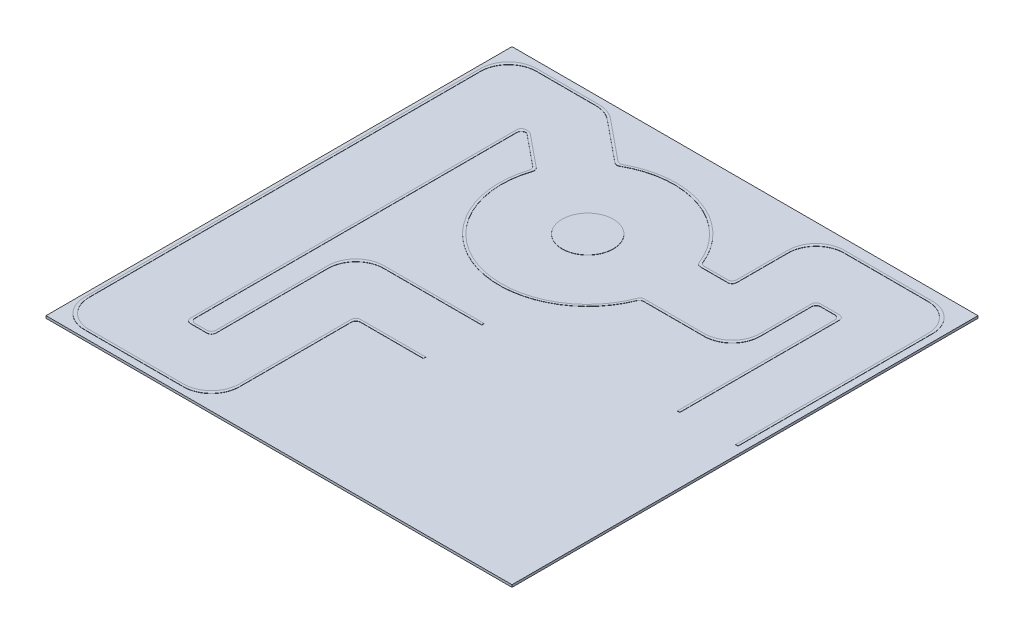
SolidWorks part; units mm, degrees
ref_plane "Plan de face" through (0, 0, 0) normal (0, 0, 1) x (1, 0, 0)
ref_plane "Plan de dessus" through (0, 0, 0) normal (0, 1, 0) x (1, 0, 0)
ref_plane "Plan de droite" through (0, 0, 0) normal (1, 0, 0) x (0, 0, -1)
sketch "Esquisse1" plane through (0, 0, 0) normal (0, 1, 0) x (1, 0, 0)
  line L0 (840, 0) -> (840, 825) construction
  line L1 (-1000, 1000) -> (1000, 1000)
  line L2 (-1000, 1000) -> (-1000, -1000)
  line L3 (-1000, -1000) -> (1000, -1000)
  line L4 (1000, 1000) -> (1000, -1000)
  line L5 (840, 825) -> (480, 825) construction
  line L6 (480, 825) -> (480, 465) construction
  line L7 (480, 465) -> (-140, 465) construction
  line L8 (-140, 465) -> (-600, 840) construction
  line L9 (-600, 840) -> (-800, 840) construction
  line L10 (-800, 840) -> (-800, -840) construction
  line L11 (-800, -840) -> (-450, -840) construction
  line L12 (-450, -840) -> (-450, -220) construction
  line L13 (-450, -220) -> (-30, -220) construction
  line L14 (720, 0) -> (720, 685)
  line L15 (700, 705) -> (620, 705)
  line L16 (600, 685) -> (600, 465)
  line L17 (480, 345) -> (224.0055, 345)
  line L18 (710, 0) -> (710, 675)
  line L19 (690, 695) -> (630, 695)
  line L20 (610, 675) -> (610, 455)
  line L21 (490, 335) -> (230.8099, 335)
  line L22 (710, 0) -> (710, 695) construction
  line L23 (960, 0) -> (960, 825)
  line L24 (840, 945) -> (480, 945)
  line L25 (360, 825) -> (360, 605)
  line L26 (340, 585) -> (224.0055, 585)
  line L27 (970, 0) -> (970, 835)
  line L28 (850, 955) -> (470, 955)
  line L29 (350, 835) -> (350, 615)
  line L30 (330, 595) -> (230.8099, 595)
  line L31 (-30, -340) -> (-310, -340)
  line L32 (-330, -360) -> (-330, -840)
  line L33 (-450, -960) -> (-855, -960)
  line L34 (-975, -840) -> (-975, 840)
  line L35 (-855, 960) -> (-600, 960)
  line L36 (-524.1767, 933.0099) -> (-346.3109, 788.0105)
  line L37 (-30, -100) -> (-450, -100)
  line L38 (-570, -220) -> (-570, -700)
  line L39 (-590, -720) -> (-660, -720)
  line L40 (-680, -700) -> (-680, 700)
  line L41 (-660, 720) -> (-649.8346, 720)
  line L42 (-637.1974, 715.5016) -> (-497.9574, 601.9908)
  line L43 (710, 0) -> (720, 0)
  line L44 (960, 0) -> (970, 0)
  line L45 (-30, -90) -> (-460, -90)
  line L46 (-580, -210) -> (-580, -690)
  line L47 (-600, -710) -> (-650, -710)
  line L48 (-670, -690) -> (-670, 690)
  line L49 (-650, 710) -> (-646.275, 710)
  line L50 (-646.275, 710) -> (-509.55, 598.5394)
  line L51 (-30, -350) -> (-300, -350)
  line L52 (-320, -370) -> (-320, -850)
  line L53 (-440, -970) -> (-865, -970)
  line L54 (-985, -850) -> (-985, 850)
  line L55 (-865, 970) -> (-596.4404, 970)
  line L56 (-520.6171, 943.0099) -> (-345.2663, 800.0608)
  line L57 (-30, -90) -> (-30, -100)
  line L58 (-30, -340) -> (-30, -350)
  line L59 (-553.725, 970) -> (-329.1369, 786.9118) construction
  line L60 (-646.275, 710) -> (-493.4206, 585.3905) construction
  line L61 (350, 595) -> (210, 595) construction
  line L62 (610, 335) -> (210, 335) construction
  line L63 (960, 0) -> (960, 945) construction
  line L64 (960, 945) -> (360, 945) construction
  line L65 (970, 0) -> (970, 955) construction
  line L66 (970, 955) -> (350, 955) construction
  line L67 (350, 955) -> (350, 595) construction
  line L68 (360, 945) -> (360, 585) construction
  line L69 (610, 695) -> (610, 335) construction
  line L70 (600, 705) -> (600, 345) construction
  line L71 (600, 345) -> (210, 345) construction
  line L72 (-30, -100) -> (-570, -100) construction
  line L73 (-570, -100) -> (-570, -720) construction
  line L74 (-30, -90) -> (-580, -90) construction
  line L75 (-580, -90) -> (-580, -710) construction
  line L76 (-330, -340) -> (-330, -960) construction
  line L77 (-330, -960) -> (-975, -960) construction
  line L78 (-320, -350) -> (-320, -970) construction
  line L79 (-320, -970) -> (-985, -970) construction
  line L80 (-975, -960) -> (-975, 960) construction
  line L81 (-985, -970) -> (-985, 970) construction
  line L82 (-985, 970) -> (-553.725, 970) construction
  line L83 (-975, 960) -> (-557.2847, 960) construction
  line L84 (-557.2847, 960) -> (-335.4555, 779.161) construction
  line L85 (710, 695) -> (610, 695) construction
  line L86 (720, 705) -> (600, 705) construction
  line L87 (720, 0) -> (720, 705) construction
  line L88 (-30, -340) -> (-330, -340) construction
  line L89 (-30, -350) -> (-320, -350) construction
  line L90 (-580, -710) -> (-670, -710) construction
  line L91 (-570, -720) -> (-680, -720) construction
  line L92 (-680, -720) -> (-680, 720) construction
  line L93 (-670, -710) -> (-670, 710) construction
  line L94 (-680, 720) -> (-642.7153, 720) construction
  line L95 (-642.7153, 720) -> (-487.102, 593.1413) construction
  line L96 (-670, 710) -> (-646.275, 710) construction
  line L97 (360, 585) -> (210, 585) construction
  circle A0 centre (-140, 465) radius 110
  circle A1 centre (-140, 465) radius 120
  arc A2 (-491.5898, 580.259) -> (205.3385, 332.1795) centre (-140, 465) ccw
  arc A3 (-503.0779, 577.1359) -> (212.2694, 322.5) centre (-140, 465) ccw
  arc A4 (212.2694, 607.5) -> (-322.9976, 798.0343) centre (-140, 465) ccw
  arc A5 (205.3385, 597.8205) -> (-323.7417, 786.1526) centre (-140, 465) ccw
  arc A6 (960, 825) -> (840, 945) centre (840, 825) ccw
  arc A7 (970, 835) -> (850, 955) centre (850, 835) ccw
  arc A8 (470, 955) -> (350, 835) centre (470, 835) ccw
  arc A9 (480, 945) -> (360, 825) centre (480, 825) ccw
  arc A10 (610, 455) -> (490, 335) centre (490, 455) cw
  arc A11 (600, 465) -> (480, 345) centre (480, 465) cw
  arc A12 (-450, -100) -> (-570, -220) centre (-450, -220) ccw
  arc A13 (-460, -90) -> (-580, -210) centre (-460, -210) ccw
  arc A14 (-330, -840) -> (-450, -960) centre (-450, -840) cw
  arc A15 (-320, -850) -> (-440, -970) centre (-440, -850) cw
  arc A16 (-855, -960) -> (-975, -840) centre (-855, -840) cw
  arc A17 (-865, -970) -> (-985, -850) centre (-865, -850) cw
  arc A18 (-985, 850) -> (-865, 970) centre (-865, 850) cw
  arc A19 (-975, 840) -> (-855, 960) centre (-855, 840) cw
  arc A20 (-596.4404, 970) -> (-520.6171, 943.0099) centre (-596.4404, 850) cw
  arc A21 (-600, 960) -> (-524.1767, 933.0099) centre (-600, 840) cw
  arc A22 (630, 695) -> (610, 675) centre (630, 675) ccw
  arc A23 (620, 705) -> (600, 685) centre (620, 685) ccw
  arc A24 (720, 685) -> (700, 705) centre (700, 685) ccw
  arc A25 (710, 675) -> (690, 695) centre (690, 675) ccw
  arc A26 (-310, -340) -> (-330, -360) centre (-310, -360) ccw
  arc A27 (-300, -350) -> (-320, -370) centre (-300, -370) ccw
  arc A28 (-580, -690) -> (-600, -710) centre (-600, -690) cw
  arc A29 (-570, -700) -> (-590, -720) centre (-590, -700) cw
  arc A30 (-660, -720) -> (-680, -700) centre (-660, -700) cw
  arc A31 (-650, -710) -> (-670, -690) centre (-650, -690) cw
  arc A32 (-649.8346, 720) -> (-637.1974, 715.5016) centre (-649.8346, 700) cw
  arc A33 (-680, 700) -> (-660, 720) centre (-660, 700) cw
  arc A34 (-670, 690) -> (-650, 710) centre (-650, 690) cw
  arc A35 (-503.0779, 577.1359) -> (-509.55, 598.5394) centre (-522.1872, 583.0378) ccw
  arc A36 (-497.9574, 601.9908) -> (-491.5898, 580.259) centre (-510.5946, 586.4892) cw
  arc A37 (-322.9976, 798.0343) -> (-345.2663, 800.0608) centre (-332.6291, 815.5625) cw
  arc A38 (-346.3109, 788.0105) -> (-323.7417, 786.1526) centre (-333.6737, 803.5122) ccw
  arc A39 (212.2694, 322.5) -> (230.8099, 335) centre (230.8099, 315) cw
  arc A40 (224.0055, 345) -> (205.3385, 332.1795) centre (224.0055, 325) ccw
  arc A41 (224.0055, 585) -> (205.3385, 597.8205) centre (224.0055, 605) cw
  arc A42 (212.2694, 607.5) -> (230.8099, 595) centre (230.8099, 615) ccw
  arc A43 (360, 605) -> (340, 585) centre (340, 605) cw
  arc A44 (350, 615) -> (330, 595) centre (330, 615) cw
  point P176 (210, 585)
  dimension "D18" = 220
  dimension "D19" = 240
  dimension "D20" = 740
  dimension "D21" = 760
  dimension "D50" = 120
  dimension "D51" = 120
  dimension "D52" = 120
  dimension "D53" = 120
  dimension "D54" = 120
  dimension "D55" = 20
  dimension "D56" = 20
  dimension "D1" = 2000
  dimension "D2" = 2000
  dimension "D3" = 1000
  dimension "D4" = 1000
  dimension "D5" = 1000
  dimension "D6" = 175
  dimension "D7" = 160
  dimension "D8" = 160
  dimension "D9" = 360
  dimension "D10" = 360
  dimension "D11" = 620
  dimension "D12" = 160
  dimension "D13" = 200
  dimension "D14" = 620
  dimension "D15" = 420
  dimension "D16" = 550
  dimension "D17" = 200
  dimension "D22" = 120
  dimension "D23" = 120
  dimension "D24" = 120
  dimension "D25" = 120
  dimension "D27" = 120
  dimension "D28" = 120
  dimension "D29" = 120
  dimension "D30" = 120
  dimension "D32" = 120
  dimension "D33" = 120
  dimension "D34" = 175
  dimension "D35" = 120
  dimension "D36" = 120
  dimension "D37" = 120
  dimension "D38" = 120
  dimension "D39" = 120
  dimension "D40" = 120
  dimension "D41" = 120
  dimension "D42" = 120
  dimension "D43" = 120
  dimension "D44" = 10
  dimension "D46" = 0
  dimension "D47" = 0
  dimension "D48" = 0
  dimension "D49" = 0
  dimension "D26" = 10
  dimension "D31" = 10
  dimension "D45" = 10
sketch "Esquisse2" plane through (0, 0, 0) normal (0, 1, 0) x (1, 0, 0)
  line L1 (-1000, 1000) -> (1000, 1000)
  line L2 (-1000, 1000) -> (-1000, -1000)
  line L3 (-1000, -1000) -> (1000, -1000)
  line L4 (1000, 1000) -> (1000, -1000)
extrude "Boss.-Extru.2" add sketch "Esquisse2" against normal blind 10 contours L2 L1 L4 L3
extrude "Boss.-Extru.6" add sketch "Esquisse1" along normal blind 1 contours A0 | L37 A12 L38 A29 L39 A30 L40 A33 L41 A32 L42 A36 A2 A40 L17 A11 L16 A23 L15 A24 L14 L43 L18 A25 L19 A22 L20 A10 L21 A39 A3 A35 L50 L49 A34 L48 A31 L47 A28 L46 A13 L45 L57 | L31 A26 L32 A14 L33 A16 L34 A19 L35 A21 L36 A38 A5 A41 L26 A43 L25 A9 L24 A6 L23 L44 L27 A7 L28 A8 L29 A44 L30 A42 A4 A37 L56 A20 L55 A18 L54 A17 L53 A15 L52 A27 L51 L58
